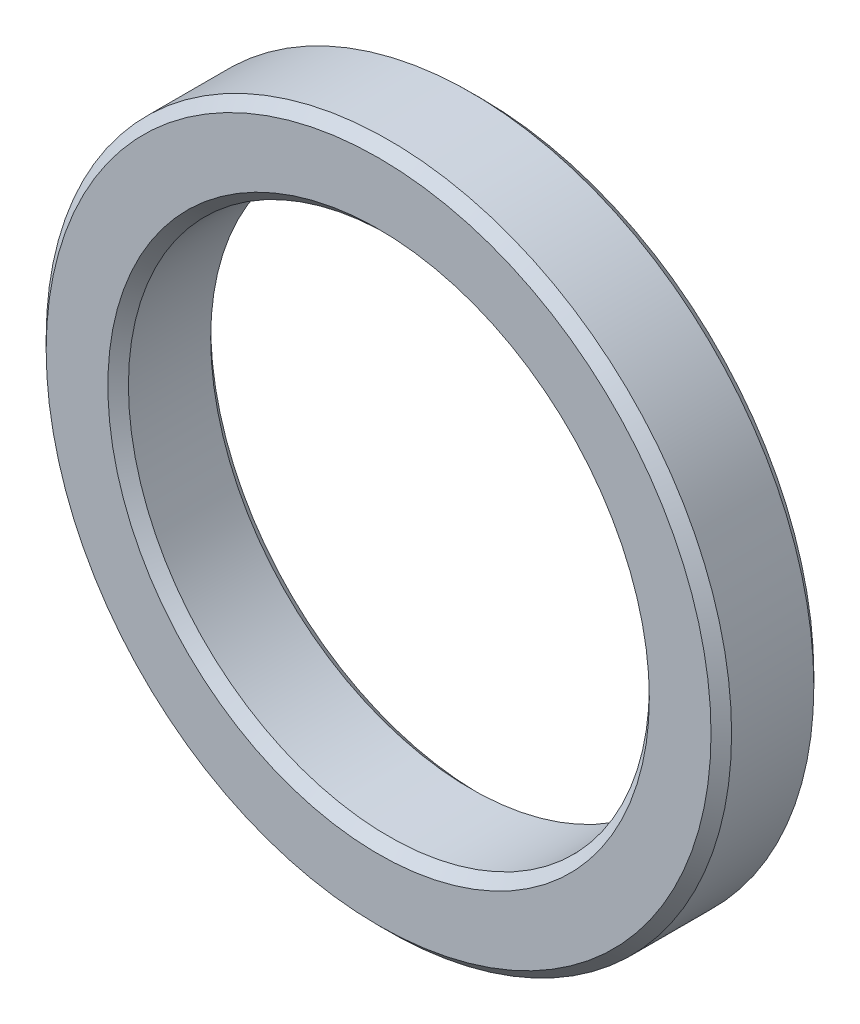
SolidWorks part; units mm, degrees
ref_plane "前视基准面" through (0, 0, 0) normal (0, 0, 1) x (1, 0, 0)
ref_plane "上视基准面" through (0, 0, 0) normal (0, 1, 0) x (1, 0, 0)
ref_plane "右视基准面" through (0, 0, 0) normal (1, 0, 0) x (0, 0, -1)
sketch "草图1" plane through (0, 0, 0) normal (0, 0, 1) x (1, 0, 0)
  circle A0 centre (0, 0) radius 10
  circle A1 centre (0, 0) radius 7.6
  dimension "D1" = 20
extrude "拉伸1" add sketch "草图1" along normal blind 3
chamfer "倒角1" distance 0.3 angle 45 4 edges at (10, 0, 0) (10, 0, 3) (7.6, 0, 0) (7.6, 0, 3)
